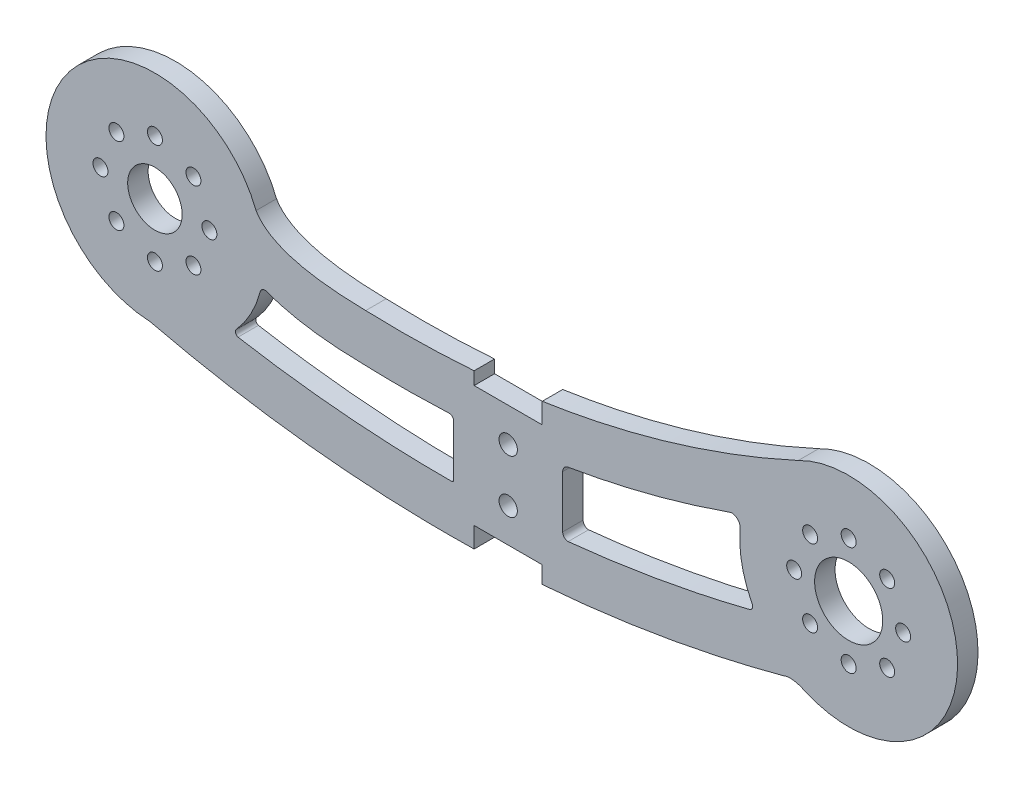
SolidWorks part; units mm, degrees
material "1060-H12"
ref_plane "Front Plane" through (0, 0, 0) normal (0, 0, 1) x (1, 0, 0)
ref_plane "Top Plane" through (0, 0, 0) normal (0, 1, 0) x (1, 0, 0)
ref_plane "Right Plane" through (0, 0, 0) normal (1, 0, 0) x (0, 0, -1)
sketch "Sketch1" plane through (0, 0, 0) normal (0, 0, 1) x (1, 0, 0)
  circle A0 centre (75.3616, -26.747) radius 5
  circle A1 centre (75.3616, -18.747) radius 1.1
  circle A2 centre (81.0185, -21.0901) radius 1.1
  circle A3 centre (83.3616, -26.747) radius 1.1
  circle A4 centre (-26.5181, -26.5149) radius 4
  circle A5 centre (81.0185, -32.4038) radius 1.1
  circle A6 centre (-26.5165, -18.5165) radius 1.1
  circle A7 centre (-20.8597, -20.8597) radius 1.1
  circle A8 centre (-18.5165, -26.5165) radius 1.1
  circle A9 centre (-20.8597, -32.1734) radius 1.1
  circle A10 centre (-26.5165, -34.5165) radius 1.1
  circle A11 centre (-32.1734, -32.1734) radius 1.1
  circle A12 centre (-34.5165, -26.5165) radius 1.1
  circle A13 centre (-32.1734, -20.8597) radius 1.1
  circle A14 centre (75.3616, -34.747) radius 1.1
  circle A15 centre (69.7048, -32.4038) radius 1.1
  circle A16 centre (67.3616, -26.747) radius 1.1
  circle A17 centre (69.7048, -21.0901) radius 1.1
  arc A22 (-11.6583, -20.5832) -> (-27.2644, -42.4975) centre (-26.5181, -26.5149) ccw
  arc A23 (68.9359, -41.3999) -> (67.9573, -12.5633) centre (75.3616, -26.747) ccw
  spline S0 degree 2 poles (-11.6583, -20.5832) (-9.0657, -25.06) (4.4406, -25.2547) knots 0 0 0 1 1 1
  spline S1 degree 2 poles (68.9359, -41.3999) (67.0568, -40.5293) (65.8717, -41.0057) knots 0 0 0 1 1 1
  spline S4 degree 3 poles (-27.2644, -42.4975) (-25.3345, -42.9558) (-21.4523, -43.8161) (-13.7054, -45.2869) (-4.0064, -46.6675) (7.6383, -47.5868) (19.2892, -47.7688) (30.9419, -47.2128) (42.5916, -45.92) (52.2982, -44.2285) (60.0522, -42.5101) (63.9403, -41.5254) (65.8717, -41.0057) knots 0.004189 0.004189 0.004189 0.004189 0.066428 0.128666 0.253142 0.377618 0.502095 0.626571 0.751047 0.875524 0.937762 1 1 1 1
  spline S7 degree 3 poles (67.9573, -12.5633) (65.4556, -13.7139) (60.3648, -15.8829) (52.6836, -18.6413) (44.8961, -20.9333) (37.0154, -22.753) (29.0339, -24.103) (20.9508, -24.9835) (14.1236, -25.3251) (8.6146, -25.3641) (5.8288, -25.3031) (4.4406, -25.2547) knots 0.003419 0.003419 0.003419 0.003419 0.119867 0.236316 0.352765 0.469214 0.585663 0.702111 0.81856 0.876785 0.935009 0.935009 0.935009 0.935009
  dimension "D1" = 8
  dimension "D2" = 8
  dimension "D3" = 8
  dimension "D4" = 10
extrude "Boss-Extrude1" add sketch "Sketch1" along normal blind 3
sketch "Sketch2" plane through (0, 0, 3) normal (0, 0, 1) x (1, 0, 0)
  line L0 (20.3616, -26.8313) -> (30.3616, -26.8313)
  line L1 (30.3616, -23.8313) -> (20.3616, -23.8313)
  line L2 (30.3616, -23.8313) -> (30.3616, -26.8313)
  line L4 (20.3616, -23.8313) -> (20.3616, -26.8313)
  line L5 (20.3616, -47.6255) -> (30.3616, -47.6255)
  line L6 (20.3616, -47.6255) -> (20.3616, -44.6255)
  line L8 (30.3616, -47.6255) -> (30.3616, -44.6255)
  line L9 (20.3616, -44.6255) -> (30.3616, -44.6255)
  circle A1 centre (25.3616, -31.8313) radius 1.35
  circle A2 centre (25.3616, -39.6255) radius 1.35
  circle A3 centre (75.3616, -26.747) radius 5 construction
  spline S0 degree 3 poles (67.9573, -12.5633) (65.4556, -13.7139) (60.3648, -15.8829) (52.6836, -18.6413) (44.8961, -20.9333) (37.0154, -22.753) (29.0339, -24.103) (20.9508, -24.9835) (14.1236, -25.3251) (8.6146, -25.3641) (5.8288, -25.3031) (4.4406, -25.2547) knots 0.003419 0.003419 0.003419 0.003419 0.119867 0.236316 0.352765 0.469214 0.585663 0.702111 0.81856 0.876785 0.935009 0.935009 0.935009 0.935009 construction
  spline S2 degree 3 poles (-27.2644, -42.4975) (-25.3345, -42.9558) (-21.4523, -43.8161) (-13.7054, -45.2869) (-4.0064, -46.6675) (7.6383, -47.5868) (19.2892, -47.7688) (30.9419, -47.2128) (42.5916, -45.92) (52.2982, -44.2285) (60.0522, -42.5101) (63.9403, -41.5254) (65.8717, -41.0057) knots 0.004189 0.004189 0.004189 0.004189 0.066428 0.128666 0.253142 0.377618 0.502095 0.626571 0.751047 0.875524 0.937762 1 1 1 1 construction
  dimension "D6" = 8
  dimension "D5" = 45
  dimension "D1" = 10
  dimension "D2" = 3
  dimension "D3" = 45
  dimension "D4" = 3
  dimension "D7" = 8
  dimension "D8" = 5
  dimension "D9" = 5
extrude "Cut-Extrude2" cut sketch "Sketch2" against normal blind 5
sketch "Sketch3" plane through (0, 0, 3) normal (0, 0, 1) x (1, 0, 0)
  line L1 (17.3616, -32.8476) -> (17.3616, -40.364)
  line L5 (33.3616, -31.2788) -> (33.3616, -38.9497)
  arc A0 (59.4146, -25.4453) -> (61.1867, -34.1679) centre (75.3616, -26.747) ccw
  arc A1 (-14.5511, -37.1353) -> (-11.0439, -30.583) centre (-26.5181, -26.5149) ccw
  arc A2 (-10.1763, -30.0811) -> (-11.0439, -30.583) centre (-10.3611, -30.7625) ccw
  arc A3 (-14.5511, -37.1353) -> (-14.3127, -38.0146) centre (-14.1438, -37.4968) ccw
  arc A4 (17.3616, -32.8476) -> (16.7006, -32.1844) centre (16.6983, -32.8476) ccw
  arc A5 (17.0899, -40.6679) -> (17.3616, -40.364) centre (17.0559, -40.364) ccw
  arc A6 (34.044, -30.3346) -> (33.3616, -31.2788) centre (34.356, -31.2788) ccw
  arc A7 (33.3616, -38.9497) -> (34.1651, -39.772) centre (34.1841, -38.9497) ccw
  arc A8 (59.4146, -25.4453) -> (58.0678, -24.1217) centre (58.1891, -25.3452) ccw
  arc A9 (60.8864, -35.0698) -> (61.1867, -34.1679) centre (60.6018, -34.4741) ccw
  spline S0 degree 3 poles (2923.278, -678.9537) (423.5953, 131.8802) (81.353, -41.6793) (-3.4922, -31.7193) (-4.4979, -31.5677) (-6.4408, -31.1961) (-7.3781, -30.9762) (-9.1979, -30.4482) (-10.0807, -30.1402) (-11.802, -29.401) (-12.6415, -28.9695) (-14.2663, -27.9294) (-15.0528, -27.3189) (-41.8893, -0.5859) (11.1881, 176.0212) (2953.98, -381.7389) knots -9.767633 -9.767633 -9.767633 -9.767633 0.25 0.25 0.375 0.375 0.5 0.5 0.625 0.625 0.75 0.75 0.875 0.875 5.364546 5.364546 5.364546 5.364546 only from (4.3398, -32.254) to (-17.7158, -24.0912)
  spline S1 degree 3 poles (4.2676, -32.2529) (1.8526, -32.2162) (-0.3759, -32.0851) (-3.4922, -31.7193) (-4.4979, -31.5677) (-6.4408, -31.1961) (-7.3781, -30.9762) (-8.9304, -30.5258) (-9.5592, -30.3175) (-10.1763, -30.0811) knots 0.002465 0.002465 0.002465 0.002465 0.25 0.25 0.375 0.375 0.5 0.5 0.588246 0.588246 0.588246 0.588246
  spline S4 degree 3 poles (2948.1076, -411.3886) (-263.432, 124.8982) (-134.6188, -13.4384) (-18.0027, -37.347) (-16.0935, -37.7074) (-10.3633, -38.6961) (-6.5413, -39.2317) (331.4006, -75.6363) (664.1979, 835.5355) (1298.8093, 2645.953) knots -7.37356 -7.37356 -7.37356 -7.37356 0.125 0.125 0.25 0.25 0.5 0.5 22.359776 22.359776 22.359776 22.359776 only from (-25.6473, -35.6869) to (20.2085, -40.6271)
  spline S5 degree 3 poles (-14.3127, -38.0146) (-14.2697, -38.022) (-14.2266, -38.0295) (-10.3633, -38.6961) (-6.5413, -39.2317) (3.8829, -40.3547) (10.4855, -40.6961) (17.0899, -40.6679) knots 0.247179 0.247179 0.247179 0.247179 0.25 0.25 0.5 0.5 0.932004 0.932004 0.932004 0.932004
  spline S7 degree 3 poles (-2821.7511, -785.7208) (299.8446, 270.7559) (188.9236, 25.3771) (57.9987, -24.1892) (54.738, -25.2934) (-243.8955, -114.7801) (-749.9797, 763.2605) (-934.9087, 2738.5332) knots -9.59558 -9.59558 -9.59558 -9.59558 0.25 0.25 0.5 0.5 22.935709 22.935709 22.935709 22.935709 only from (70.8822, -18.9229) to (31.393, -30.7549)
  spline S8 degree 3 poles (58.0678, -24.1217) (55.8723, -24.8957) (53.6665, -25.6144) (45.7238, -27.9945) (39.9215, -29.3465) (34.044, -30.3346) knots 0.331394 0.331394 0.331394 0.331394 0.5 0.5 0.934761 0.934761 0.934761 0.934761
  spline S10 degree 3 poles (-1205.1497, 2660.6745) (-623.4673, 828.1026) (-293.9368, -96.8808) (49.7864, -37.5344) (52.6379, -36.9735) (56.9166, -36.0286) (58.3441, -35.6961) (168.2996, -8.7595) (277.6298, 117.1676) (-2891.2734, -537.5114) knots -29.378685 -29.378685 -29.378685 -29.378685 0.5 0.5 0.75 0.75 0.875 0.875 10.367992 10.367992 10.367992 10.367992 only from (29.8298, -40.1553) to (64.0532, -34.2461)
  spline S11 degree 3 poles (34.1651, -39.772) (38.42, -39.3437) (42.6763, -38.762) (49.7864, -37.5344) (52.6379, -36.9735) (56.9166, -36.0286) (58.3441, -35.6961) (60.1443, -35.2551) (60.5154, -35.163) (60.8864, -35.0698) knots 0.126769 0.126769 0.126769 0.126769 0.5 0.5 0.75 0.75 0.875 0.875 0.907464 0.907464 0.907464 0.907464
  spline S12 degree 3 poles (-966.6613, 2700.4355) (426.3004, 717.0451) (286.1936, -27.0364) (11.1985, -32.3468) (9.8035, -32.3545) (-89.3305, -31.5113) (-201.0667, 64.1716) (2967.2384, -498.137) knots -48.706644 -48.706644 -48.706644 -48.706644 0.5 0.5 0.75 0.75 18.177892 18.177892 18.177892 18.177892 only from (20.8863, -31.9295) to (4.1967, -32.2505)
  spline S13 degree 3 poles (16.7006, -32.1844) (15.3334, -32.2482) (13.9627, -32.2934) (11.1985, -32.3468) (9.8035, -32.3545) (7.0232, -32.3309) (5.6422, -32.3003) (4.2676, -32.2529) knots 0.252875 0.252875 0.252875 0.252875 0.5 0.5 0.75 0.75 0.995779 0.995779 0.995779 0.995779
  dimension "D1" = 7
  dimension "D2" = 7
  dimension "D3" = 7
  dimension "D4" = 7
  dimension "D5" = 7
extrude "Cut-Extrude3" cut sketch "Sketch3" against normal blind 3
sketch "Sketch4" plane through (0, 0, 3) normal (0, 0, 1) x (1, 0, 0)
  point P0 (-26.5181, -26.5149)
sketch "Sketch5" plane through (0, 0, 3) normal (0, 0, 1) x (1, 0, 0)
  line L0 (-26.5181, -26.5149) -> (75.3616, -26.747) construction
  point P4 (24.4218, -26.631)
